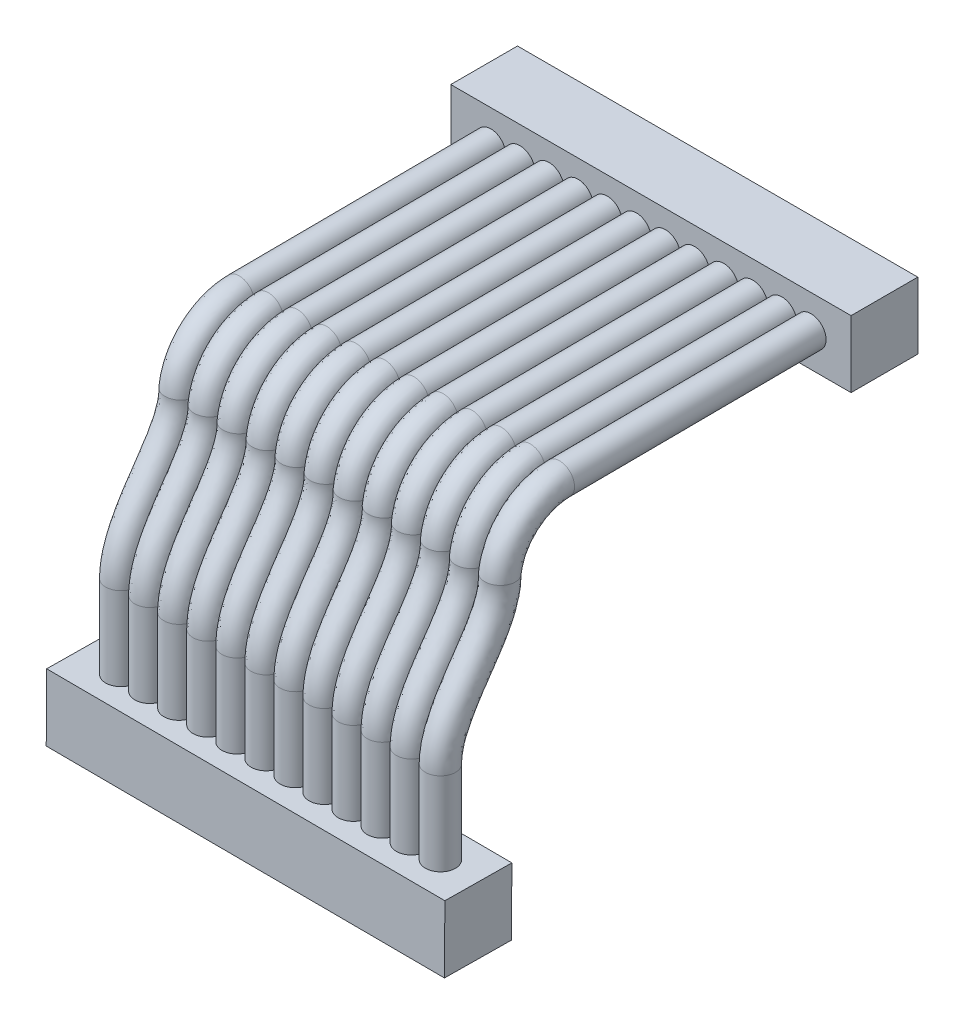
SolidWorks part; units mm, degrees
ref_plane "Front Plane" through (0, 0, 0) normal (0, 0, 1) x (1, 0, 0)
ref_plane "Top Plane" through (0, 0, 0) normal (0, 1, 0) x (1, 0, 0)
ref_plane "Right Plane" through (0, 0, 0) normal (1, 0, 0) x (0, 0, -1)
sketch "Sketch1" plane through (0, 0, 0) normal (0, 1, 0) x (1, 0, 0)
  line L1 (0, 0) -> (30.48, 0)
  line L2 (0, 0) -> (0, 5.08)
  line L3 (0, 5.08) -> (30.48, 5.08)
  line L4 (30.48, 0) -> (30.48, 5.08)
  dimension "D1" = 30.48
  dimension "D2" = 5.08
extrude "Boss-Extrude1" add sketch "Sketch1" along normal blind 5.08
sketch "Sketch2" plane through (0, 0, 0) normal (0, -1, 0) x (1, 0, 0)
  line L14 (0.508, -0.508) -> (0.508, -4.572)
  line L15 (29.972, -0.508) -> (0.508, -0.508)
  line L16 (29.972, -4.572) -> (29.972, -0.508)
  line L17 (0.508, -4.572) -> (29.972, -4.572)
  line L18 (0.508, -0.508) -> (0.508, -4.572)
  line L19 (29.972, -0.508) -> (0.508, -0.508)
  line L20 (29.972, -4.572) -> (29.972, -0.508)
  line L21 (0.508, -4.572) -> (29.972, -4.572)
  dimension "D1" = 0.508
extrude "Cut-Extrude1" cut sketch "Sketch2" against normal blind 3.81
sketch "Sketch3" plane through (0, 5.08, 0) normal (0, 0, -1) x (1, 0, 0)
  line L0 (0, 2.54) -> (30.48, 2.54) construction
  line L3 (0, 0) -> (0, 5.08) construction
  line L5 (30.48, 0) -> (30.48, 5.08) construction
  arc A0 (4.1564, 2.8192) -> (4.1564, 2.2608) centre (3.048, 2.54) ccw
  arc A1 (4.1564, 2.2608) -> (6.3731, 2.2608) centre (5.2647, 2.54) ccw
  arc A2 (6.3731, 2.2608) -> (8.5898, 2.2608) centre (7.4815, 2.54) ccw
  arc A3 (8.5898, 2.2608) -> (10.8065, 2.2608) centre (9.6982, 2.54) ccw
  arc A4 (10.8065, 2.2608) -> (13.0233, 2.2608) centre (11.9149, 2.54) ccw
  arc A5 (13.0233, 2.2608) -> (15.24, 2.2608) centre (14.1316, 2.54) ccw
  arc A6 (15.24, 2.2608) -> (17.4567, 2.2608) centre (16.3484, 2.54) ccw
  arc A7 (17.4567, 2.2608) -> (19.6735, 2.2608) centre (18.5651, 2.54) ccw
  arc A8 (19.6735, 2.2608) -> (21.8902, 2.2608) centre (20.7818, 2.54) ccw
  arc A9 (21.8902, 2.2608) -> (24.1069, 2.2608) centre (22.9985, 2.54) ccw
  arc A10 (24.1069, 2.2608) -> (26.3236, 2.2608) centre (25.2153, 2.54) ccw
  arc A11 (26.3236, 2.2608) -> (26.3236, 2.8192) centre (27.432, 2.54) ccw
  arc A12 (6.3731, 2.8192) -> (4.1564, 2.8192) centre (5.2647, 2.54) ccw
  arc A13 (8.5898, 2.8192) -> (6.3731, 2.8192) centre (7.4815, 2.54) ccw
  arc A14 (10.8065, 2.8192) -> (8.5898, 2.8192) centre (9.6982, 2.54) ccw
  arc A15 (13.0233, 2.8192) -> (10.8065, 2.8192) centre (11.9149, 2.54) ccw
  arc A16 (15.24, 2.8192) -> (13.0233, 2.8192) centre (14.1316, 2.54) ccw
  arc A17 (17.4567, 2.8192) -> (15.24, 2.8192) centre (16.3484, 2.54) ccw
  arc A18 (19.6735, 2.8192) -> (17.4567, 2.8192) centre (18.5651, 2.54) ccw
  arc A19 (21.8902, 2.8192) -> (19.6735, 2.8192) centre (20.7818, 2.54) ccw
  arc A20 (24.1069, 2.8192) -> (21.8902, 2.8192) centre (22.9985, 2.54) ccw
  arc A21 (26.3236, 2.8192) -> (24.1069, 2.8192) centre (25.2153, 2.54) ccw
  dimension "D4" = 2.286
  dimension "D2" = 3.048
  dimension "D3" = 3.048
  dimension "D1" = 12
sketch3d "3DSketch2"
  line L0 (3.048, 2.54, 0) -> (3.048, 2.4173, 19.1521)
  line L3 (3.048, -11.8864, 28.1774) -> (3.048, -18.2131, 28.1774)
  arc A1 (3.048, 2.4173, 19.1521) -> (3.04, -1.608, 23.6551) centre (3.0389, -2.1467, 19.1229) ccw
  spline S1 degree 3 poles (3.04, -1.608, 23.6551) (3.0443, -4.7134, 23.5316) (3.048, -7.924, 28.1774) (3.048, -11.8864, 28.1774) knots 0.806714 0.806714 0.806714 0.806714 1 1 1 1
  point P4 (7.603, -2.1558, 19.1228)
surface "Surface-Sweep1"
surface "Surface-Fill1"
sketch "Sketch4" plane through (-0.0002, -18.3928, 0.1178) normal (0, -1, 0.0064) x (1, 0, 0.0044)
  line L2 (1.905, 27.9805) -> (28.6988, 27.9805) construction
  line L3 (0, 30.5205) -> (30.4573, 30.5205)
  line L4 (0, 30.5205) -> (0, 25.4405)
  line L5 (0, 25.4405) -> (30.4573, 25.4405)
  line L6 (30.4573, 30.5205) -> (30.4573, 25.4405)
  arc A1 (26.4467, 27.7071) -> (26.4481, 28.2656) centre (27.5558, 27.9835) ccw construction
  dimension "D1" = 5.08
  dimension "D2" = 2.54
extrude "Boss-Extrude2" add sketch "Sketch4" along normal blind 5.08 separate body
sketch "Sketch5" plane through (-0.0003, -23.4727, 0.1503) normal (0, 1, -0.0064) x (1, 0, 0.0044)
  line L14 (29.9493, -30.0125) -> (29.9493, -25.9485)
  line L15 (29.9493, -25.9485) -> (0.508, -25.9485)
  line L16 (0.508, -25.9485) -> (0.508, -30.0125)
  line L17 (0.508, -30.0125) -> (29.9493, -30.0125)
  line L18 (29.9493, -30.0125) -> (29.9493, -25.9485)
  line L19 (29.9493, -25.9485) -> (0.508, -25.9485)
  line L20 (0.508, -25.9485) -> (0.508, -30.0125)
  line L21 (0.508, -30.0125) -> (29.9493, -30.0125)
  dimension "D1" = 0.508
extrude "Cut-Extrude2" cut sketch "Sketch5" along normal blind 4.572
equation "\"D2@Sketch4\"=.1"
